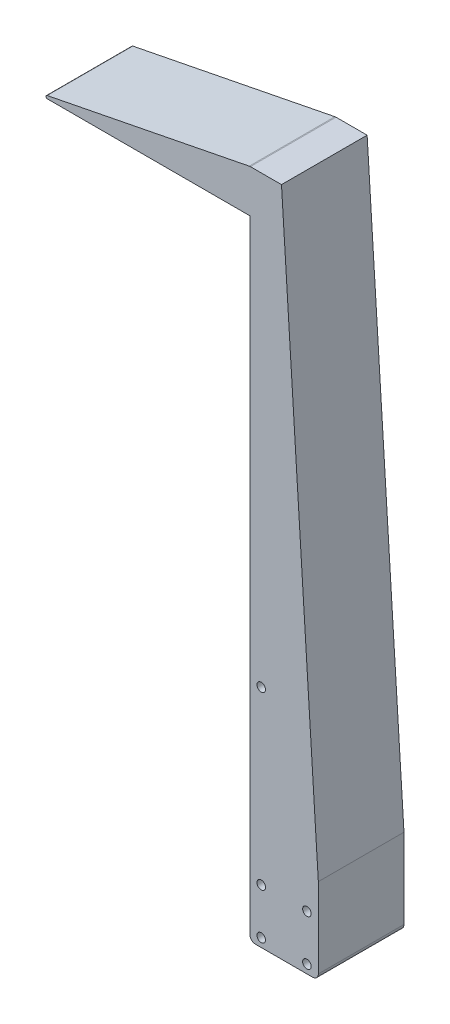
SolidWorks part; units mm, degrees
ref_plane "前视基准面" through (0, 0, 0) normal (0, 0, 1) x (1, 0, 0)
ref_plane "上视基准面" through (0, 0, 0) normal (0, 1, 0) x (1, 0, 0)
ref_plane "右视基准面" through (0, 0, 0) normal (1, 0, 0) x (0, 0, -1)
other "Configuration Table"
sketch "草图1" plane through (0, 0, 0) normal (0, 0, 1) x (1, 0, 0)
  line L1 (2, 0) -> (22, 0)
  line L2 (0, 2) -> (0, 220)
  line L4 (24, 2) -> (24, 220)
  line L5 (0, 220) -> (-70.8845, 220)
  line L6 (24, 220) -> (24, 233)
  line L7 (22, 235) -> (0.1955, 235)
  line L9 (-0.1918, 234.9621) -> (-70.9813, 220.9905)
  arc A0 (-0.1918, 234.9621) -> (0.1955, 235) centre (0.1955, 233) cw
  arc A1 (24, 233) -> (22, 235) centre (22, 233) ccw
  arc A2 (22, 0) -> (24, 2) centre (22, 2) ccw
  arc A3 (2, 0) -> (0, 2) centre (2, 2) cw
  arc A4 (-70.8845, 220) -> (-70.9813, 220.9905) centre (-70.8845, 220.5) cw
  circle A5 centre (20, 3) radius 1.5
  circle A6 centre (4, 3) radius 1.5
  circle A7 centre (4, 19) radius 1.5
  circle A9 centre (20, 19) radius 1.5 [skipped]
  point P12 (24, 235)
  point P15 (24, 0)
  point P18 (0, 0)
  dimension "D4" = 2
  dimension "D5" = 0.5
  dimension "D8" = 3
  dimension "D1" = 220
  dimension "D2" = 24
  dimension "D3" = 15
  dimension "D6" = 3
  dimension "D7" = 4
  dimension "D9" = 2
  dimension "D10" = 2
extrude "凸台-拉伸1" add sketch "草图1" along normal blind 30
sketch "草图2" plane through (0, 0, 30) normal (0, 0, 1) x (1, 0, 0)
  line L6 (24, 2) -> (24, 233)
  line L7 (22, 235) -> (0.1955, 235)
  line L8 (-0.1918, 234.9621) -> (-70.9813, 220.9905)
  line L9 (-70.8845, 220) -> (0, 220)
  line L10 (0, 220) -> (0, 2)
  line L11 (2, 0) -> (22, 0)
  line L12 (24, 2) -> (24, 233)
  line L13 (22, 235) -> (0.1955, 235)
  line L14 (-0.1918, 234.9621) -> (-70.9813, 220.9905)
  line L15 (-70.8845, 220) -> (0, 220)
  line L16 (0, 220) -> (0, 2)
  line L17 (2, 0) -> (22, 0)
  circle A0 centre (20, 3) radius 1.5 construction
  circle A1 centre (4, 3) radius 1.5 construction
  circle A2 centre (4, 19) radius 1.5 construction
  circle A3 centre (20, 3) radius 1.5
  circle A4 centre (4, 3) radius 1.5
  arc A5 (24, 233) -> (22, 235) centre (22, 233) ccw
  arc A6 (0.1955, 235) -> (-0.1918, 234.9621) centre (0.1955, 233) ccw
  arc A7 (-70.9813, 220.9905) -> (-70.8845, 220) centre (-70.8845, 220.5) ccw
  arc A8 (0, 2) -> (2, 0) centre (2, 2) ccw
  arc A9 (22, 0) -> (24, 2) centre (22, 2) ccw
  arc A10 (24, 233) -> (22, 235) centre (22, 233) ccw
  arc A11 (0.1955, 235) -> (-0.1918, 234.9621) centre (0.1955, 233) ccw
  arc A12 (-70.9813, 220.9905) -> (-70.8845, 220) centre (-70.8845, 220.5) ccw
  arc A13 (0, 2) -> (2, 0) centre (2, 2) ccw
  arc A14 (22, 0) -> (24, 2) centre (22, 2) ccw
  circle A15 centre (4, 19) radius 1.5
  circle A16 centre (4, 3) radius 1.5
  circle A18 centre (20, 19) radius 1.5
  circle A19 centre (4, 19) radius 1.5 [skipped]
  dimension "D1" = 0
  dimension "D2" = 2
  dimension "D3" = 2
extrude "切除-拉伸1" cut sketch "草图2" against normal through all contours A18
sketch "草图3" plane through (0, 0, 0) normal (0, 0, -1) x (-1, 0, 0)
  line L0 (-24, 30) -> (-11.0977, 235)
  line L1 (-24, 2) -> (-24, 233) construction
  line L2 (-22, 235) -> (-0.1955, 235) construction
  line L3 (-11.0977, 235) -> (-26.8669, 235)
  line L4 (-26.8669, 235) -> (-24, 30)
  line L5 (-2, 0) -> (-22, 0) construction
  dimension "D1" = 30
extrude "切除-拉伸2" cut sketch "草图3" against normal through all
sketch "草图4" plane through (0, 0, 0) normal (0, 0, -1) x (-1, 0, 0)
  circle A0 centre (-4, 79) radius 1.5
extrude "切除-拉伸3" cut sketch "草图4" against normal through all
